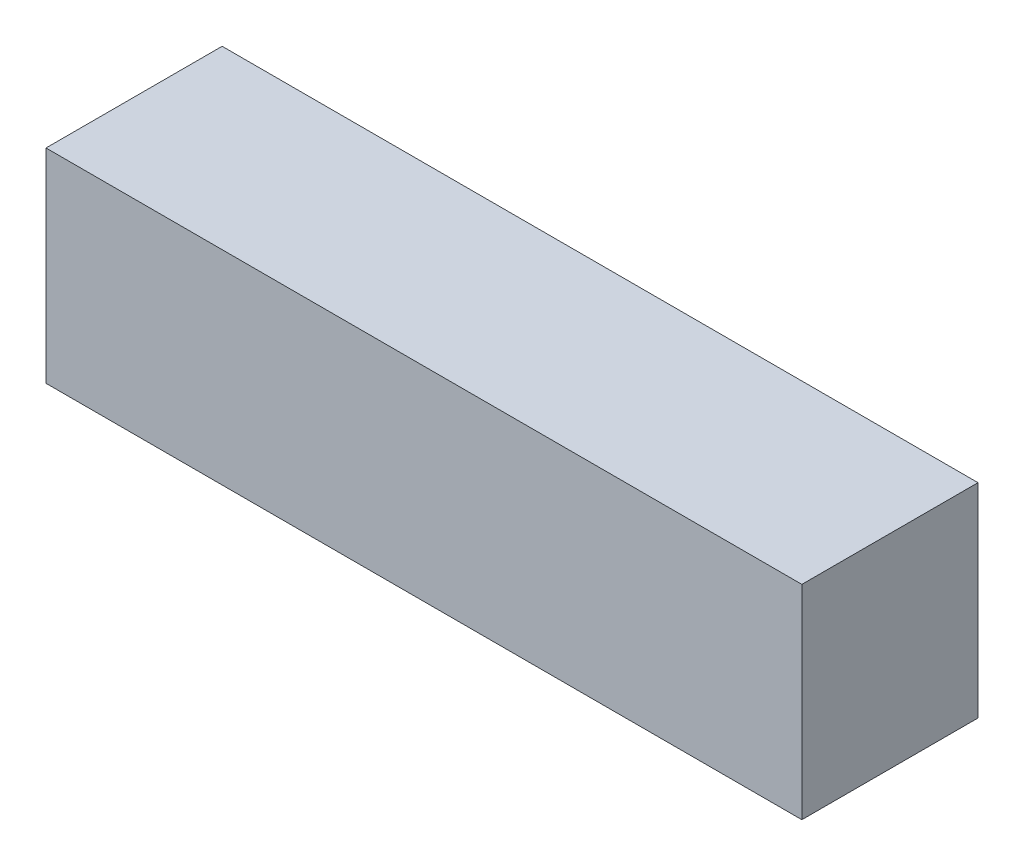
SolidWorks part; units mm, degrees
ref_plane "Front Plane" through (0, 0, 0) normal (0, 0, 1) x (1, 0, 0)
ref_plane "Top Plane" through (0, 0, 0) normal (0, 1, 0) x (1, 0, 0)
ref_plane "Right Plane" through (0, 0, 0) normal (1, 0, 0) x (0, 0, -1)
sketch "Sketch2" plane through (0, 0, 0) normal (0, 0, 1) x (1, 0, 0)
  line L1 (0, 0) -> (103.9876, 0)
  line L2 (0, 0) -> (0, 28.0416)
  line L3 (0, 28.0416) -> (103.9876, 28.0416)
  line L4 (103.9876, 0) -> (103.9876, 28.0416)
  dimension "D1" = 28.0416
  dimension "D2" = 103.9876
extrude "Boss-Extrude1" add sketch "Sketch2" along normal blind 24.2316
